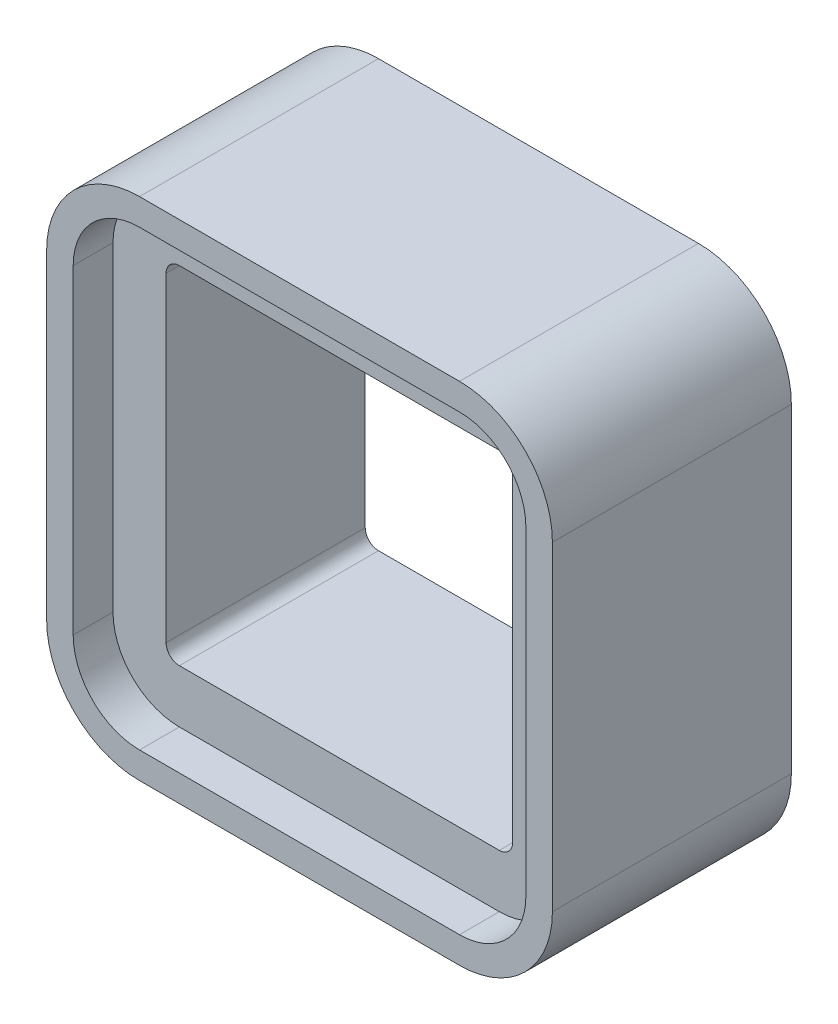
SolidWorks part; units mm, degrees
ref_plane "Ebene vorne" through (0, 0, 0) normal (0, 0, 1) x (1, 0, 0)
ref_plane "Ebene oben" through (0, 0, 0) normal (0, 1, 0) x (1, 0, 0)
ref_plane "Ebene rechts" through (0, 0, 0) normal (1, 0, 0) x (0, 0, -1)
sketch "Skizze1" plane through (0, 0, 0) normal (0, 0, 1) x (1, 0, 0)
  line L1 (17.05, -17.05) -> (-17.05, -17.05)
  line L2 (17.05, -17.05) -> (17.05, 17.05)
  line L3 (17.05, 17.05) -> (-17.05, 17.05)
  line L4 (-17.05, -17.05) -> (-17.05, 17.05)
  line L5 (17.05, -17.05) -> (-17.05, 17.05) construction
  line L6 (17.05, 17.05) -> (-17.05, -17.05) construction
  line L7 (19.05, -19.05) -> (-19.05, -19.05)
  line L8 (19.05, -19.05) -> (19.05, 19.05)
  line L9 (19.05, 19.05) -> (-19.05, 19.05)
  line L10 (-19.05, -19.05) -> (-19.05, 19.05)
  line L11 (19.05, -19.05) -> (-19.05, 19.05) construction
  line L12 (19.05, 19.05) -> (-19.05, -19.05) construction
  point P0 (0, 0)
  point P6 (0, 0)
  dimension "D1" = 34.1
  dimension "D2" = 34.1
  dimension "D3" = 2
  dimension "D4" = 2
extrude "Aufsatz-Linear austragen1" add sketch "Skizze1" along normal blind 3
sketch "Skizze2" plane through (0, 0, 0) normal (0, 0, -1) x (-1, 0, 0)
  line L1 (-19.05, 19.05) -> (19.05, 19.05)
  line L2 (-19.05, 19.05) -> (-19.05, -19.05)
  line L3 (-19.05, -19.05) -> (19.05, -19.05)
  line L4 (19.05, 19.05) -> (19.05, -19.05)
extrude "Aufsatz-Linear austragen2" add sketch "Skizze2" along normal blind 15
fillet "Verrundung1" radius 5 4 edges at (-17.05, -17.05, 1.5) (-17.05, 17.05, 1.5) (17.05, 17.05, 1.5) (17.05, -17.05, 1.5)
fillet "Verrundung2" radius 7 4 edges at (19.05, -19.05, -6) (-19.05, -19.05, -6) (-19.05, 19.05, -6) (19.05, 19.05, -6)
sketch "Skizze3" plane through (0, 0, 0) normal (0, 0, 1) x (1, 0, 0)
  line L8 (-13.05, 12.05) -> (-13.05, -12.05)
  line L9 (-12.05, -13.05) -> (12.05, -13.05)
  line L10 (13.05, -12.05) -> (13.05, 12.05)
  line L11 (12.05, 13.05) -> (-12.05, 13.05)
  line L12 (-13.05, 12.05) -> (-13.05, -12.05)
  line L13 (-12.05, -13.05) -> (12.05, -13.05)
  line L14 (13.05, -12.05) -> (13.05, 12.05)
  line L15 (12.05, 13.05) -> (-12.05, 13.05)
  arc A8 (-13.05, -12.05) -> (-12.05, -13.05) centre (-12.05, -12.05) ccw
  arc A9 (12.05, -13.05) -> (13.05, -12.05) centre (12.05, -12.05) ccw
  arc A10 (13.05, 12.05) -> (12.05, 13.05) centre (12.05, 12.05) ccw
  arc A11 (-12.05, 13.05) -> (-13.05, 12.05) centre (-12.05, 12.05) ccw
  arc A12 (-13.05, -12.05) -> (-12.05, -13.05) centre (-12.05, -12.05) ccw
  arc A13 (12.05, -13.05) -> (13.05, -12.05) centre (12.05, -12.05) ccw
  arc A14 (13.05, 12.05) -> (12.05, 13.05) centre (12.05, 12.05) ccw
  arc A15 (-12.05, 13.05) -> (-13.05, 12.05) centre (-12.05, 12.05) ccw
  dimension "D1" = 4
extrude "Schnitt-Linear austragen1" cut sketch "Skizze3" against normal blind 15
